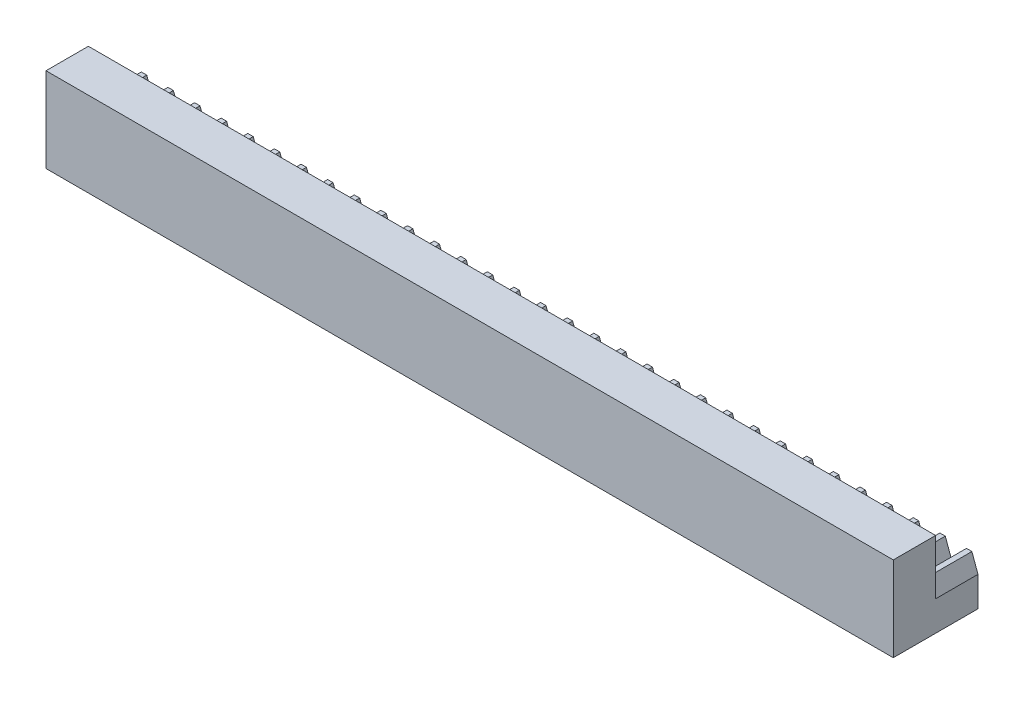
SolidWorks part; units mm, degrees
extrude "Blank" add sketch "BlankSke" against normal blind 10
sketch "BlankSke" plane through (0, 0, 0) normal (0, 0, 1) x (1, 0, 0)
  line L1 (0, 0) -> (200, 0)
  line L2 (0, 0) -> (0, 11)
  line L3 (0, 11) -> (200, 11)
  line L4 (200, 0) -> (200, 11)
  dimension "Length" = 200
  dimension "Blank_height" = 11
ref_plane "Plane1" through (0, 0, 0) normal (0, 0, 1) x (1, 0, 0)
ref_plane "Plane2" through (0, 0, 0) normal (0, 1, 0) x (1, 0, 0)
ref_plane "Plane3" through (0, 0, 0) normal (1, 0, 0) x (0, 0, -1)
sketch "HoldingSke" plane through (0, 0, 0) normal (0, 1, 0) x (1, 0, 0)
  line L0 (0, 0) -> (0.0696, 0.4951)
  line L1 (-15, 0) -> (100, 0) construction
  line L2 (0, 0) -> (-2.1039, 2.3779)
  line L3 (0, 0) -> (-11.863, 4.5341)
  line L4 (0, 0) -> (7.2428, 4.7035)
  line L5 (0, 0) -> (-23.7986, -8.8762)
  line L6 (0, 0) -> (-10.5278, -7.1032)
  line L9 (-71.009, 38.7566) -> (116.9296, 107.1606)
  line L10 (-76.2, 4.3779) -> (-67.2, 4.3779)
  line L11 (0, 0) -> (-10, 0)
  line L12 (-76.2, 101.6) -> (-76.133, 101.6)
  line L13 (24.9733, 27.94) -> (52.9518, 28.4284)
  line L14 (24.9733, 27.94) -> (24.9743, 27.94)
  line L15 (24.9733, 27.94) -> (100.4006, 29.5858)
  circle A0 centre (0, 0) radius 19.05
  circle A1 centre (0, 0) radius 4.5
  circle A2 centre (0, 0) radius 12.7
  dimension "MPH" = 9
  dimension "Diameter" = 38.1
  dimension "Num_teeth" = 33
  dimension "Pitch" = 0.5
  dimension "Show_teeth" = 998
  dimension "Thickness" = 12.7
  dimension "Ap" = 20
  dimension "Pitch_height" = 9
  dimension "Width" = 10
  dimension "Backlash" = 0.067
  dimension "Addendum_fac" = 1
  dimension "Dedendum_fac" = 1.25
  dimension "Clearance_fac" = 0.25
  dimension "Dedendum_add" = 0.001
  dimension "Length" = 200
  dimension "Module" = 2
sketch "TooCutSkeIll" plane through (0, 0, 0) normal (0, 0, 1) x (1, 0, 0)
  line L0 (-2.4806, 10.9474) -> (-0.9819, 6.8296)
  line L1 (-0.5111, 6.5) -> (0.5111, 6.5)
  line L2 (0.9819, 6.8296) -> (2.4806, 10.9474)
  line L3 (200, 11) -> (0, 11) construction
  line L4 (0, 0) -> (0, 64.897) construction
  line L5 (-13.208, 9) -> (12.954, 9) construction
  line L6 (0, 0) -> (200, 0) construction
  line L7 (1.7718, 9) -> (1.7718, 48.7463) construction
  line L8 (-1.7718, 9) -> (-1.7718, 48.7463) construction
  line L9 (2.5558, 11) -> (2.5558, 11.0254)
  line L10 (-2.5558, 11) -> (-2.5558, 11.0254)
  line L11 (-2.5558, 11.0254) -> (2.5558, 11.0254)
  arc A0 (0.5111, 6.5) -> (0.9819, 6.8296) centre (0.5111, 7.001) ccw
  arc A1 (-0.9819, 6.8296) -> (-0.5111, 6.5) centre (-0.5111, 7.001) ccw
  arc A2 (2.5558, 11) -> (2.4806, 10.9474) centre (2.5558, 10.92) ccw
  arc A3 (-2.4806, 10.9474) -> (-2.5558, 11) centre (-2.5558, 10.92) ccw
  dimension "Pitch_height" = 9
  dimension "Addendum_plus" = 2.0254
  dimension "Pressure_angle" = 20
  dimension "Gap_width" = 3.5436
  dimension "Dedendum" = 2.5
extrude "ToothCutIll" [suppressed] cut sketch "TooCutSkeIll" against normal through all
sketch "TooCutSkeSim" plane through (0, 0, 0) normal (0, 0, 1) x (1, 0, 0)
  line L0 (0.8619, 6.5) -> (-0.8619, 6.5)
  line L1 (2.509, 11.0254) -> (0.8619, 6.5)
  line L2 (0, 17.4625) -> (0, 53.467) construction
  line L3 (2.509, 11.0254) -> (-2.509, 11.0254)
  line L6 (-2.509, 11.0254) -> (-0.8619, 6.5)
  line L9 (-1.7718, 9) -> (1.7718, 9) construction
  line L10 (0, 0) -> (200, 0) construction
  line L11 (1.7718, 9) -> (1.7718, 53.467) construction
  line L12 (-1.7718, 9) -> (-1.7718, 53.467) construction
  dimension "Pitch_height" = 9
  dimension "Addendum_plus" = 2.0254
  dimension "Pressure_angle" = 20
  dimension "Gap_width" = 3.5436
  dimension "Dedendum" = 2.5
extrude "ToothCutSim" cut sketch "TooCutSkeSim" against normal through all
pattern_linear "TeethCuts" count 32 spacing 6.2832 along (1, 0, 0) of "ToothCutIll", "ToothCutSim"
sketch "Esquisse2" plane through (0, 0, 0) normal (0, 0, 1) x (1, 0, 0)
  line L1 (0, 0) -> (200, 0)
  line L2 (0, 0) -> (0, 20)
  line L3 (0, 20) -> (200, 20)
  line L4 (200, 0) -> (200, 20)
  dimension "D1" = 200
  dimension "D2" = 20
extrude "Boss.-Extru.2" add sketch "Esquisse2" along normal blind 10
equation "' \"Module@HoldingSke\" = 6.35"
equation "' \"Num_teeth@HoldingSke\" = 12"
equation "' \"Ap@HoldingSke\" =  20"
equation "' \"Ap@HoldingSke\" = 20"
equation "' \"Width@HoldingSke\" = 0.25 * 25.4"
equation "' \"Show_teeth@HoldingSke\" = 500"
equation "' \"Backlash@HoldingSke\" = 0.009 * 25.4"
equation "' \"Addendum_fac@HoldingSke\" = 1.0"
equation "' \"Dedendum_fac@HoldingSke\" = 1.25"
equation "' \"Dedendum_add@HoldingSke\" = 0.00005 * 25.4"
equation "' \"Clearance_fac@HoldingSke\" = 0.25"
equation "' \"Pitch_height@HoldingSke\" = 1 * 25.4"
equation "' \"Length@HoldingSke\" = 4.71 * 25.4"
equation "\"Pitch@HoldingSke\" = 1 / \"Module@HoldingSke\""
equation "\"MPH@HoldingSke\" = \"Dedendum_fac@HoldingSke\" / \"Pitch@HoldingSke\" + 2 * \"Dedendum_add@HoldingSke\" + 0.002 * 25.4"
equation "\"MPH@HoldingSke\" = ((sgn( \"MPH@HoldingSke\" - \"Pitch_height@HoldingSke\")+1)*( \"MPH@HoldingSke\" - \"Pitch_height@HoldingSke\"))/2 + \"Pitch_height@HoldingSke\""
equation "\"Blank_height@BlankSke\" = \"Pitch_height@HoldingSke\" + \"Addendum_fac@HoldingSke\"  / \"Pitch@HoldingSke\" "
equation "\"Length@BlankSke\" =  \"Length@HoldingSke\""
equation "\"Face_width@Blank\" = \"Width@HoldingSke\""
equation "\"Pressure_angle@TooCutSkeIll\" = \"Ap@HoldingSke\""
equation "\"Addendum_plus@TooCutSkeIll\" =  \"Addendum_fac@HoldingSke\"  / \"Pitch@HoldingSke\" + 0.001 *25.4"
equation "\"Dedendum@TooCutSkeIll\" = \"Dedendum_fac@HoldingSke\"  / \"Pitch@HoldingSke\""
equation "\"Pitch_height@TooCutSkeIll\" =  \"MPH@HoldingSke\""
equation "\"Gap_width@TooCutSkeIll\" = 3.14159265 / 2 / \"Pitch@HoldingSke\" + 6 * \"Backlash@HoldingSke\""
equation "\"Pressure_angle@TooCutSkeSim\" = \"Ap@HoldingSke\""
equation "\"Addendum_plus@TooCutSkeSim\" =  \"Addendum_fac@HoldingSke\"  / \"Pitch@HoldingSke\" + 0.001 * 25.4"
equation "\"Dedendum@TooCutSkeSim\" = \"Dedendum_fac@HoldingSke\"  / \"Pitch@HoldingSke\""
equation "\"Pitch_height@TooCutSkeSim\" =  \"MPH@HoldingSke\""
equation "\"Gap_width@TooCutSkeSim\" = 3.14159265 / 2 / \"Pitch@HoldingSke\" + 6 * \"Backlash@HoldingSke\""
equation "\"Root_fillet@TooCutSkeIll\" = \"Clearance_fac@HoldingSke\" / \"Pitch@HoldingSke\" + \"Dedendum_add@HoldingSke\""
equation "\"Break_rad@TooCutSkeIll\" = 0.02 / \"Pitch@HoldingSke\" * 2"
equation "\"Linear_pitch@TeethCuts\" = 3.14159265 / \"Pitch@HoldingSke\""
equation "\"Num_teeth@HoldingSke\" = int( ( \"Length@HoldingSke\" + 0 ) / (3.14159265 / \"Pitch@HoldingSke\")) + 0.9999  + 1"
equation " \"Num_teeth@TeethCuts\" = int( \"Show_teeth@HoldingSke\" ) + 1"
equation " \"Num_teeth@TeethCuts\" = ((sgn( \"Num_teeth@TeethCuts\" - \"Num_teeth@HoldingSke\" )-1)*( \"Num_teeth@TeethCuts\" - \"Num_teeth@HoldingSke\" ))/-2+ \"Num_teeth@HoldingSke\""
equation " \"Num_teeth@TeethCuts\" = ((sgn( \"Num_teeth@TeethCuts\" - 2.0)+1)*( \"Num_teeth@TeethCuts\" - 2.0))/2 +2.0"
